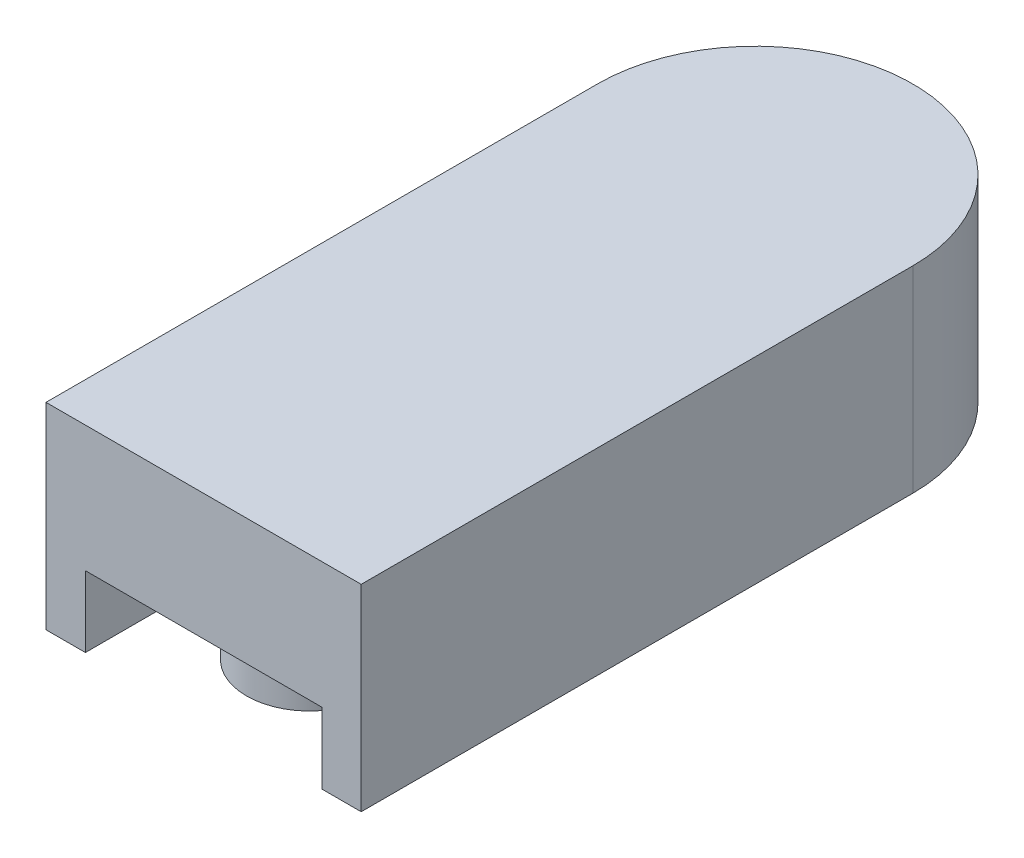
SolidWorks part; units mm, degrees
ref_plane "Plano frontal" through (0, 0, 0) normal (0, 0, 1) x (1, 0, 0)
ref_plane "Plano superior" through (0, 0, 0) normal (0, 1, 0) x (1, 0, 0)
ref_plane "Plano direito" through (0, 0, 0) normal (1, 0, 0) x (0, 0, -1)
sketch "Esboço1" plane through (0, 0, 0) normal (0, 1, 0) x (1, 0, 0)
  line L0 (-17.6667, 0) -> (-17.6667, 47.4392)
  line L1 (-17.6667, 47.4392) -> (2.3333, 47.4392)
  line L2 (2.3333, 47.4392) -> (22.3333, 47.4392)
  line L3 (22.3333, 47.4392) -> (22.3333, 0)
  line L4 (22.3333, 0) -> (22.3333, -22.5608)
  line L5 (22.3333, -22.5608) -> (2.3333, -22.5608)
  line L6 (2.3333, -22.5608) -> (-17.6667, -22.5608)
  line L7 (-17.6667, -22.5608) -> (-17.6667, 0)
  line L8 (2.3333, 47.4392) -> (2.3333, 67.4392)
  arc A0 (2.3333, 67.4392) -> (22.3333, 47.4392) centre (2.3333, 47.4392) cw
  arc A1 (2.3333, 67.4392) -> (-17.6667, 47.4392) centre (2.3333, 47.4392) ccw
  dimension "D1" = 20
  dimension "D2" = 40
  dimension "D3" = 70
extrude "Ressalto-extrusão1" add sketch "Esboço1" along normal blind 25 contours L7 L6 L5 L4 L3 L2 L1 L0 | A0 L8 L2 | L8 A1 L1
sketch "Esboço2" plane through (0, 0, 0) normal (0, 1, 0) x (1, 0, 0)
  line L1 (22.3333, -22.5608) -> (-17.6667, -22.5608) construction
  line L2 (-12.6667, -22.5608) -> (-12.6667, -9.1105)
  line L3 (-12.6667, -22.5608) -> (17.3333, -22.5608)
  line L6 (17.3333, -9.1105) -> (17.3333, -22.5608)
  arc A0 (17.3333, -9.1105) -> (-12.6667, -9.1105) centre (2.3333, -9.1105) ccw
  circle A1 centre (2.3333, -9.1105) radius 8
  dimension "D4" = 16
  dimension "D1" = 30
extrude "Corte-extrusão2" cut sketch "Esboço2" along normal blind 9
